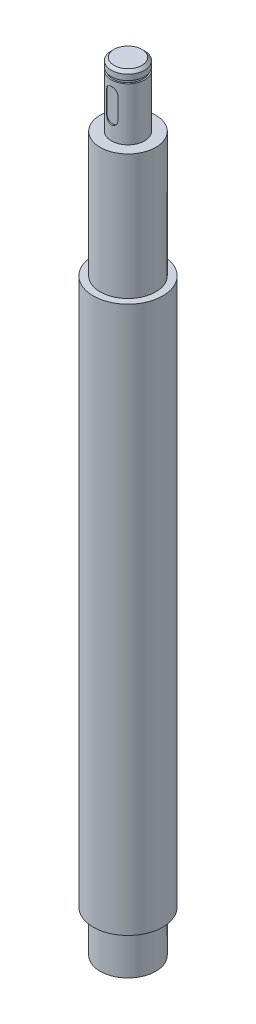
SolidWorks part; units mm, degrees
material "合金钢"
ref_plane "前视基准面" through (0, 0, 0) normal (0, 0, 1) x (1, 0, 0)
ref_plane "上视基准面" through (0, 0, 0) normal (0, 1, 0) x (1, 0, 0)
ref_plane "右视基准面" through (0, 0, 0) normal (1, 0, 0) x (0, 0, -1)
sketch "草图1" plane through (0, 0, 0) normal (0, 1, 0) x (1, 0, 0)
  circle A0 centre (0, 0) radius 12.5
  dimension "D1" = 25
extrude "凸台-拉伸1" add sketch "草图1" along normal blind 196.5
sketch "草图2" plane through (0, 0, 0) normal (0, -1, 0) x (1, 0, 0)
  circle A0 centre (0, 0) radius 10
  dimension "D1" = 20
extrude "凸台-拉伸2" add sketch "草图2" along normal blind 15
sketch "草图3" plane through (0, 196.5, 0) normal (0, 1, 0) x (1, 0, 0)
  circle A0 centre (0, 0) radius 10
  dimension "D1" = 20
extrude "凸台-拉伸3" add sketch "草图3" along normal blind 45
sketch "草图4" plane through (0, 241.5, 0) normal (0, 1, 0) x (1, 0, 0)
  circle A0 centre (0, 0) radius 6
  dimension "D1" = 6
extrude "凸台-拉伸4" add sketch "草图4" along normal blind 23
ref_plane "基准面1" through (0, 0, -6) normal (0, 0, -1) x (-1, 0, 0)
ref_plane "基准面2" through (0, 0, 9.5) normal (0, 0, -1) x (-1, 0, 0)
sketch "草图5" plane through (0, 0, 9.5) normal (0, 0, -1) x (-1, 0, 0)
  line L0 (0, 256.5) -> (0, 248.5) construction
  line L1 (2, 256.5) -> (2, 248.5)
  line L2 (-2, 256.5) -> (-2, 248.5)
  line L3 (10, 241.5) -> (-10, 241.5) construction
  arc A0 (2, 256.5) -> (-2, 256.5) centre (0, 256.5) ccw
  arc A1 (-2, 248.5) -> (2, 248.5) centre (0, 248.5) ccw
  point P3 (0, 252.5)
  point P8 (0, 246.5)
  point P9 (0, 258.5)
  dimension "D1" = 4
  dimension "D2" = 12
  dimension "D3" = 7
extrude "切除-拉伸1" cut sketch "草图5" along normal blind 4
chamfer "倒角1" distance 1 angle 45 1 edges at (0, 264.5, 6)
sketch "草图6" plane through (0, 0, 0) normal (1, 0, 0) x (0, 0, -1)
  line L0 (6, 241.5) -> (6, 263.5) construction
  line L1 (6, 260.5) -> (5.5, 260.5)
  line L2 (6, 260.5) -> (6, 261.5)
  line L3 (6, 261.5) -> (5.5, 261.5)
  line L4 (5.5, 260.5) -> (5.5, 261.5)
  line L5 (5, 264.5) -> (-5, 264.5) construction
  line L6 (0, 264.5) -> (0, 277.7152) construction
  dimension "D1" = 4
  dimension "D2" = 1
  dimension "D3" = 0.5
revolve "切除-旋转1" cut sketch "草图6" angle 360 about L6
